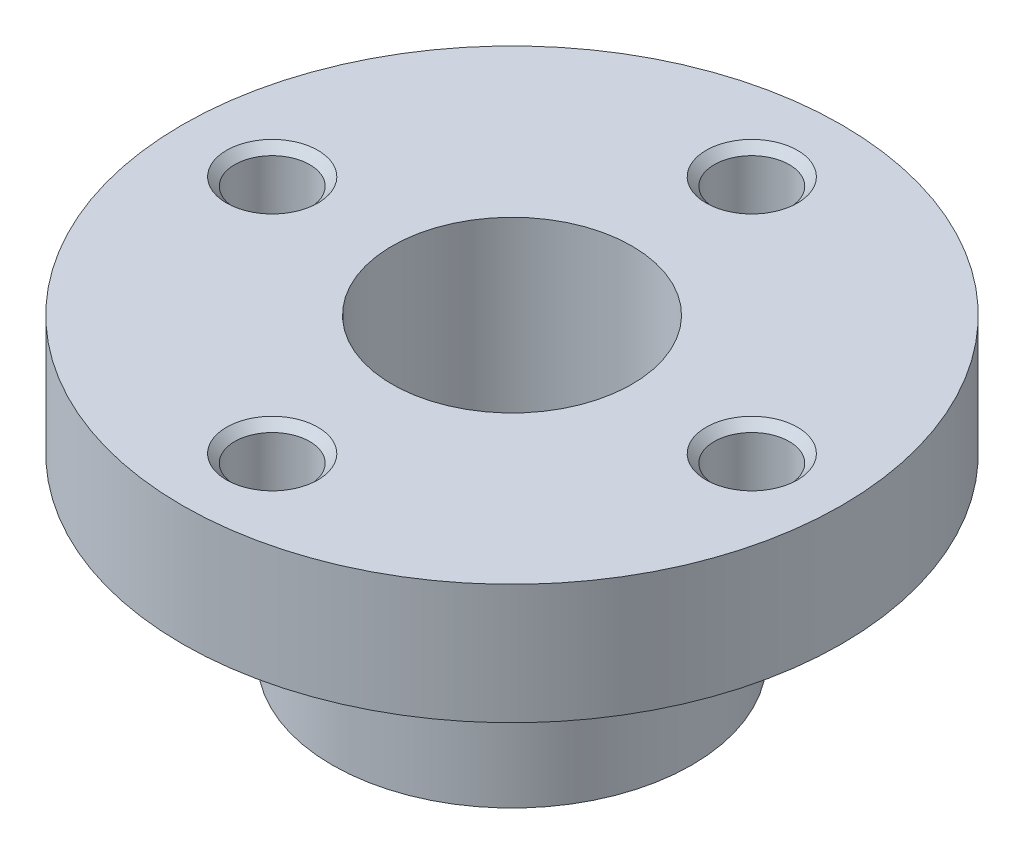
SolidWorks part; units mm, degrees
material "Brass"
ref_plane "Front Plane" through (0, 0, 0) normal (0, 0, 1) x (1, 0, 0)
ref_plane "Top Plane" through (0, 0, 0) normal (0, 1, 0) x (1, 0, 0)
ref_plane "Right Plane" through (0, 0, 0) normal (1, 0, 0) x (0, 0, -1)
sketch "Sketch1" plane through (0, 0, 0) normal (0, 0, 1) x (1, 0, 0)
  line L0 (4, 0) -> (4, 10)
  line L1 (4, 10) -> (11, 10)
  line L2 (11, 10) -> (11, 6)
  line L3 (11, 6) -> (6, 6)
  line L4 (6, 6) -> (6, 0)
  line L5 (6, 0) -> (4, 0)
  line L6 (0, 0) -> (0, 10.3863) construction
  point P9 (-0.7162, 0)
  dimension "D1" = 8
  dimension "D2" = 12
  dimension "D3" = 10
  dimension "D4" = 22
  dimension "D5" = 4
revolve "Revolve1" add sketch "Sketch1" angle 360 about L6
hole_wizard "M3x0.5 Tapped Hole1" positions "Sketch3" profile "Sketch2" tap size "M3x0.5" standard "ANSI Metric" end condition through all
sketch "Sketch3" plane through (0, 10, 0) normal (0, 1, 0) x (1, 0, 0)
  point P0 (0, 8)
  point P6 (8, 0)
  point P7 (0, -8)
  point P8 (-8, 0)
  point P9 (0, 0)
  dimension "D2" = 16
  dimension "D1" = 4
sketch "Sketch2" plane through (0, 10, -8) normal (1, 0, 0) x (0, 0, 1)
  line L0 (0, 0) -> (0, 10)
  line L1 (0, 10) -> (1.25, 10)
  line L2 (1.25, 10) -> (1.25, 0.275)
  line L3 (1.25, 0.275) -> (1.525, 0)
  line L5 (1.525, 0) -> (0, 0)
  line L6 (-1.25, 0.275) -> (-1.525, 0) construction
  line L11 (0, -6.35) -> (0, 107.95) construction
  dimension "Thread Major Dia." = 2.5
  dimension "Thru Tap Drill Depth" = 10
  dimension "Near C'Sink Dia." = 3.05
  dimension "Near C'Sink Angle" = 90
